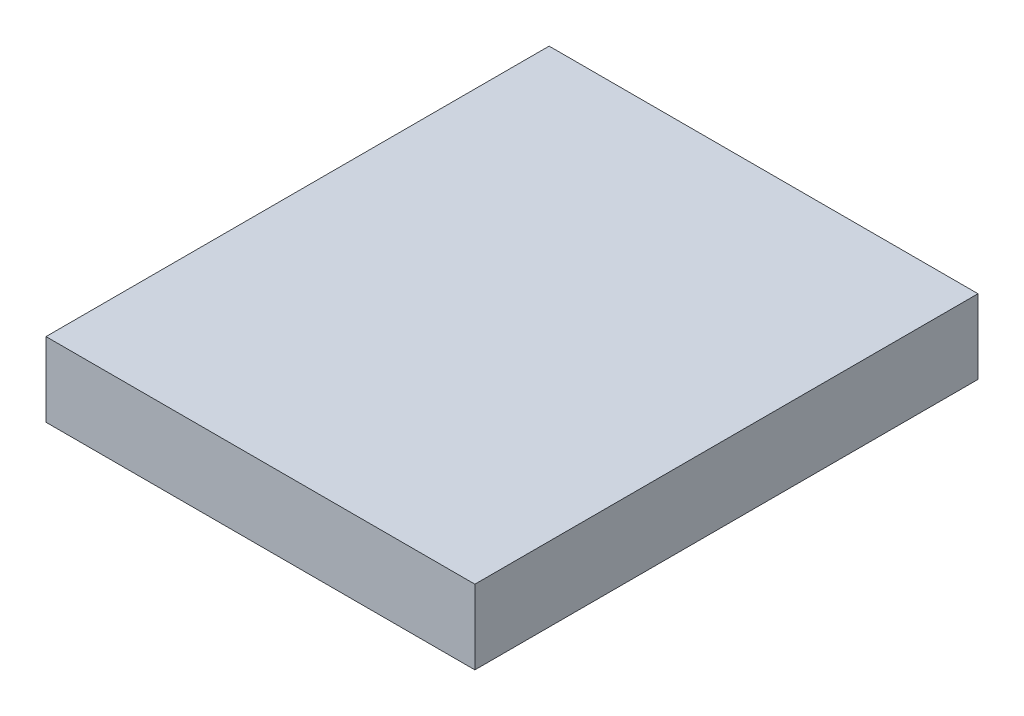
SolidWorks part; units mm, degrees
ref_plane "Front Plane" through (0, 0, 0) normal (0, 0, 1) x (1, 0, 0)
ref_plane "Top Plane" through (0, 0, 0) normal (0, 1, 0) x (1, 0, 0)
ref_plane "Right Plane" through (0, 0, 0) normal (1, 0, 0) x (0, 0, -1)
sketch "Sketch1" plane through (0, 0, 0) normal (0, 1, 0) x (1, 0, 0)
  line L1 (260, -305) -> (-260, -305)
  line L2 (260, -305) -> (260, 305)
  line L3 (260, 305) -> (-260, 305)
  line L4 (-260, -305) -> (-260, 305)
  line L5 (260, -305) -> (-260, 305) construction
  line L6 (260, 305) -> (-260, -305) construction
  point P0 (0, 0)
extrude "Boss-Extrude1" add sketch "Sketch1" along normal mid plane 90
shell "Shell1" thickness 5
